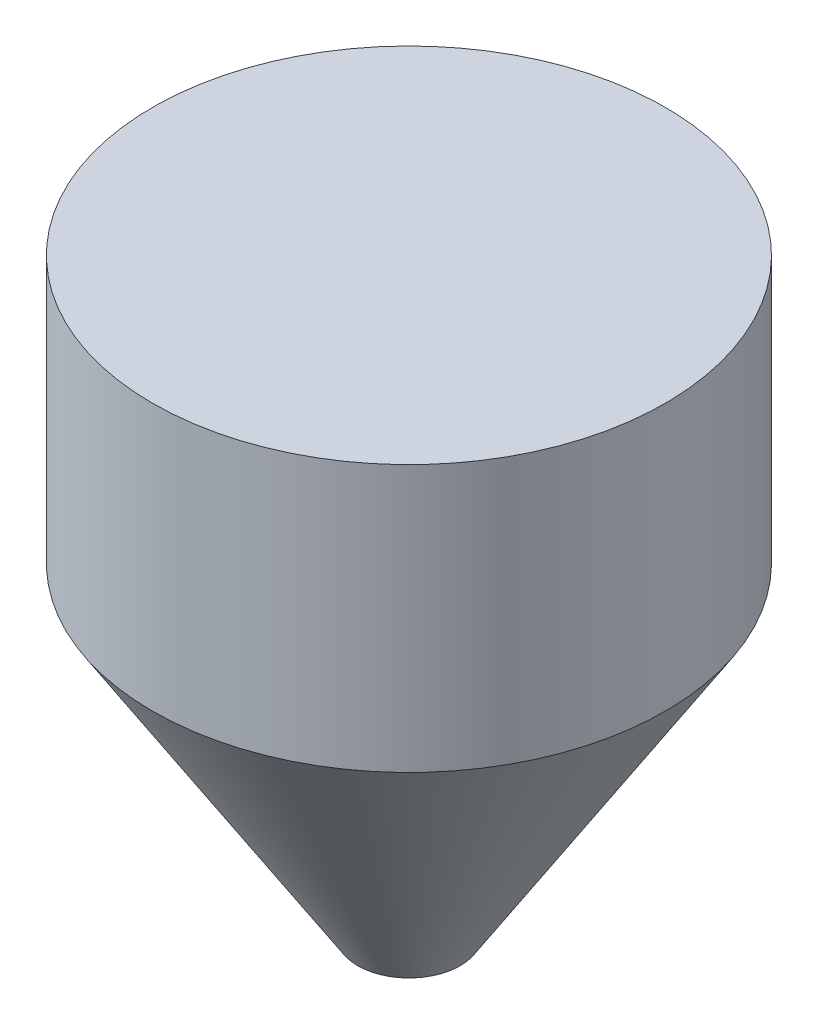
SolidWorks part; units mm, degrees
ref_plane "Alzado" through (0, 0, 0) normal (0, 0, 1) x (1, 0, 0)
ref_plane "Planta" through (0, 0, 0) normal (0, 1, 0) x (1, 0, 0)
ref_plane "Vista lateral" through (0, 0, 0) normal (1, 0, 0) x (0, 0, -1)
sketch "Croquis1" plane through (0, 0, 0) normal (0, 1, 0) x (1, 0, 0)
  circle A0 centre (0, 0) radius 100
  dimension "D1" = 200
ref_plane "Plano1" through (0, -230, 0) normal (0, 1, 0) x (1, 0, 0)
extrude "Saliente-Extruir1" add sketch "Croquis1" against normal blind 104 contours A0
sketch "Croquis2" plane through (0, -104, 0) normal (0, -1, 0) x (1, 0, 0)
  circle A2 centre (0, 0) radius 100
sketch "Croquis3" plane through (0, -230, 0) normal (0, 1, 0) x (1, 0, 0)
  circle A0 centre (0, 0) radius 20
  dimension "D1" = 40
loft "Recubrir1" add profiles "Croquis3", "Croquis2"
